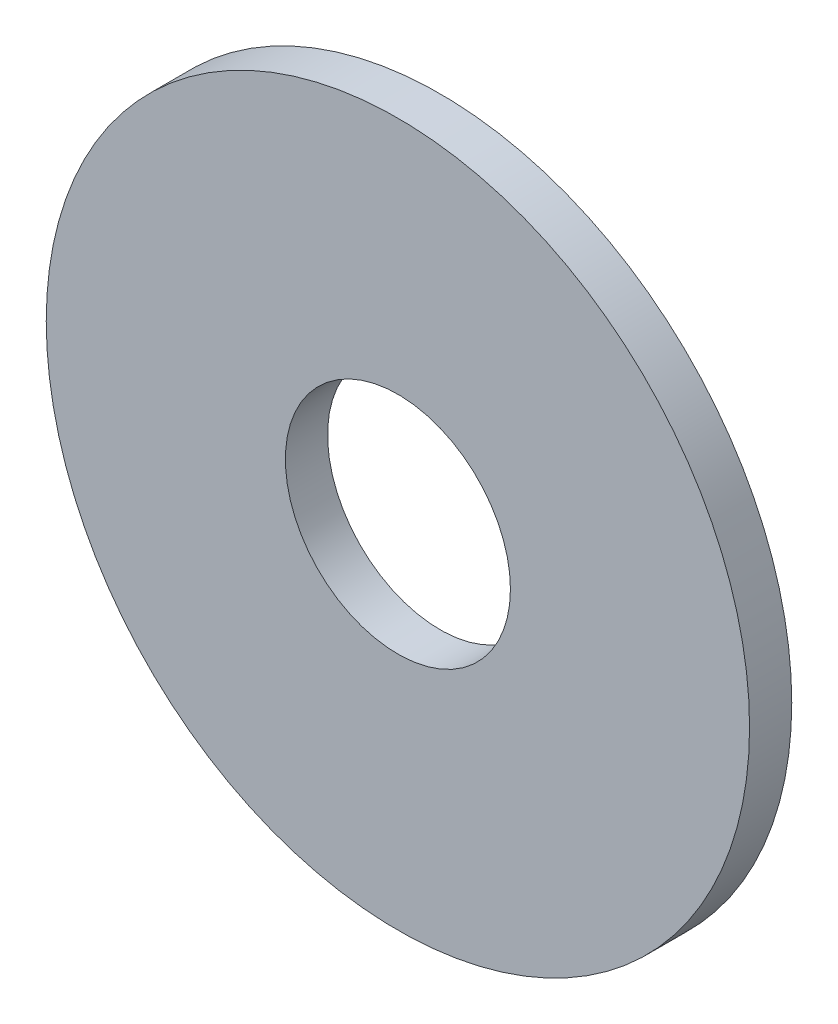
SolidWorks part; units mm, degrees
ref_plane "Front Plane" through (0, 0, 0) normal (0, 0, 1) x (1, 0, 0)
ref_plane "Top Plane" through (0, 0, 0) normal (0, 1, 0) x (1, 0, 0)
ref_plane "Right Plane" through (0, 0, 0) normal (1, 0, 0) x (0, 0, -1)
sketch "Sketch1" plane through (0, 0, 0) normal (0, 0, 1) x (1, 0, 0)
  circle A0 centre (0, 0) radius 4
  circle A1 centre (0, 0) radius 12.5
  dimension "D1" = 8
  dimension "D2" = 25
extrude "Extrude1" add sketch "Sketch1" along normal blind 1.5
